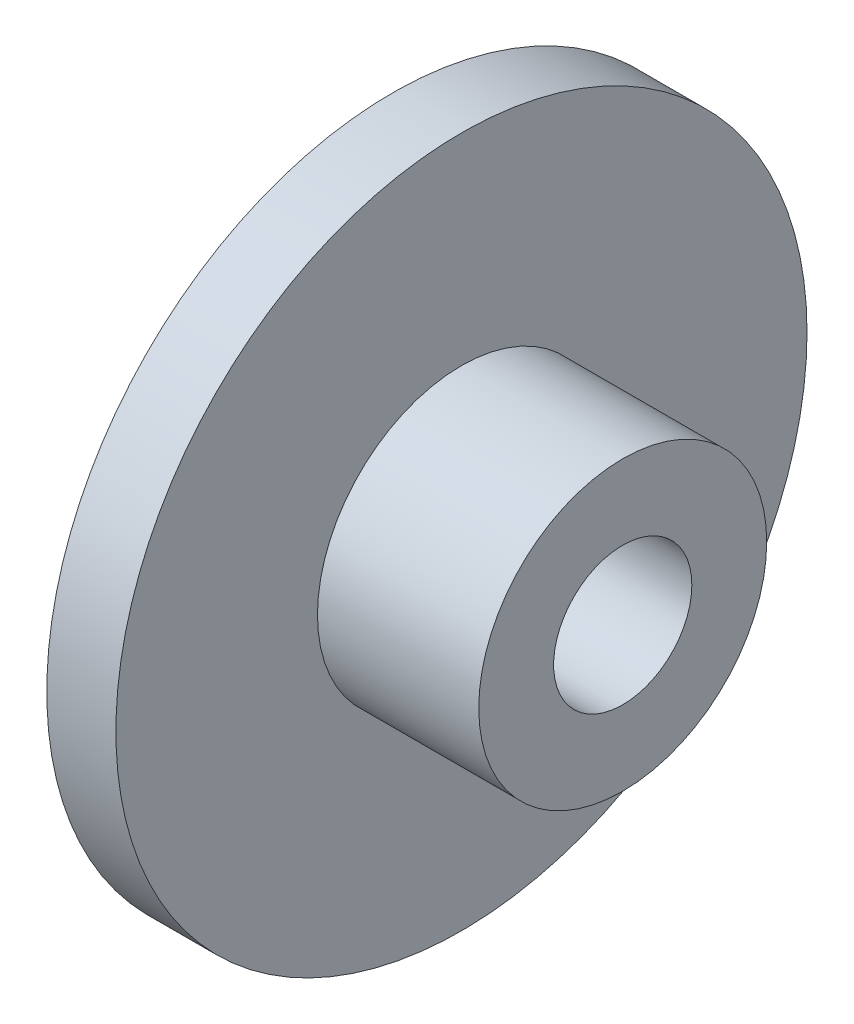
SolidWorks part; units mm, degrees
ref_plane "Front Plane" through (0, 0, 0) normal (0, 0, 1) x (1, 0, 0)
ref_plane "Top Plane" through (0, 0, 0) normal (0, 1, 0) x (1, 0, 0)
ref_plane "Right Plane" through (0, 0, 0) normal (1, 0, 0) x (0, 0, -1)
sketch "Sketch1" plane through (0, 0, 0) normal (1, 0, 0) x (0, 0, -1)
  circle A0 centre (0, 0) radius 30
  dimension "D1" = 60
extrude "Boss-Extrude1" add sketch "Sketch1" along normal mid plane 6
sketch "Sketch2" plane through (3, 0, 0) normal (1, 0, 0) x (0, 0, -1)
  circle A0 centre (0, 0) radius 12.5
  dimension "D1" = 25
extrude "Boss-Extrude2" add sketch "Sketch2" along normal blind 14
sketch "Sketch3" plane through (17, 0, 0) normal (1, 0, 0) x (0, 0, -1)
  circle A0 centre (0, 0) radius 6
  dimension "D1" = 12
extrude "Cut-Extrude1" cut sketch "Sketch3" against normal through all
sketch "SK_Pitch_Circle" plane through (0, 0, 0) normal (1, 0, 0) x (0, 0, -1)
  circle A0 centre (0, 0) radius 27.425 construction
  dimension "D1" = 54.85
equation "\"WheelDiameter\" = 150mm"
equation "\"WheelRadius\" = \"WheelDiameter\" / 2"
equation "\"DT_WheelWidth\" = 45mm"
equation "\"DT_Wheelbase\" = 300mm"
equation "\"DT_ShaftDiameter\" = 12mm"
equation "\"DT_FrontShaftLength\" = 180mm"
equation "\"DT_RearShaftLength\" = 200mm"
equation "\"DT_BearingWidth\" = 20mm"
equation "\"DT_BearingHousingWidth\" = 60mm"
equation "\"DT_BearingHousingHeight\" = 35mm"
equation "\"DT_ChainPitch\" = 9.525mm"
equation "\"DT_SprocketTeeth\" = 18"
equation "\"DT_SprocketPitchDiameter\" = 54.851mm"
equation "\"DT_SprocketOuterDiameter\" = 60mm"
equation "\"DT_SprocketThickness\" = 6mm"
equation "\"DT_SprocketHubDiameter\" = 25mm"
equation "\"DT_SprocketHubLength\" = 20mm"
equation "\"DT_CouplingDiameter\" = 30mm"
equation "\"DT_CouplingLength\" = 35mm"
equation "\"DT_MotorDiameter\" = 60mm"
equation "\"DT_MotorLength\" = 120mm"
equation "\"DT_MotorShaftDiameter\" = 8mm"
equation "\"DT_MotorShaftLength\" = 20mm"
